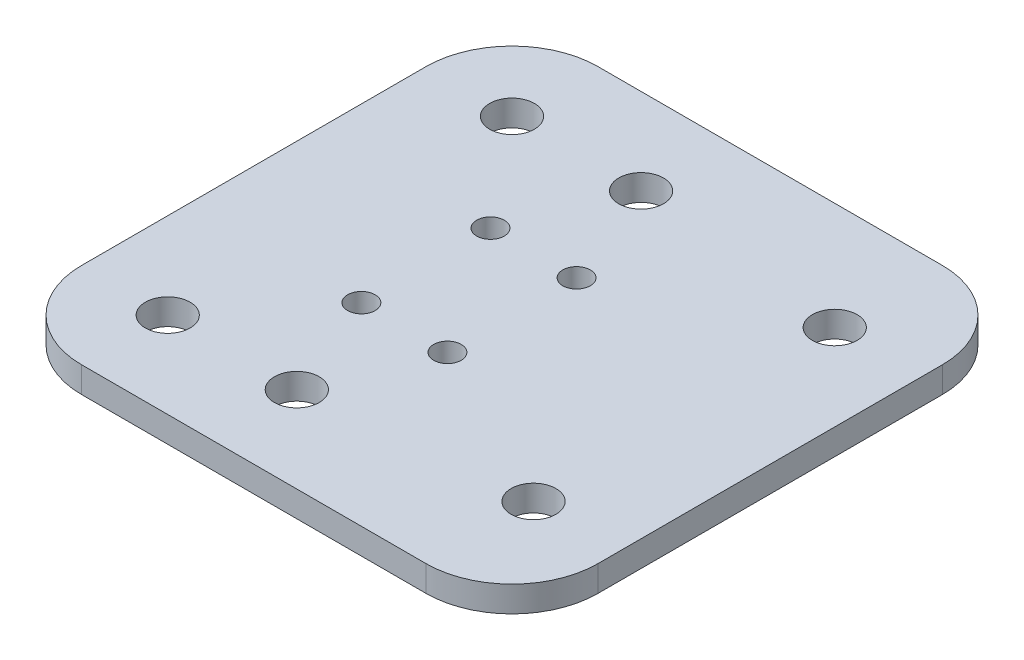
SolidWorks part; units mm, degrees
material "Thornel Mat VMA"
ref_plane "Front" through (0, 0, 0) normal (0, 0, 1) x (1, 0, 0)
ref_plane "Top" through (0, 0, 0) normal (0, 1, 0) x (1, 0, 0)
ref_plane "Right" through (0, 0, 0) normal (1, 0, 0) x (0, 0, -1)
sketch "草图1" plane through (0, 0, 0) normal (0, 1, 0) x (1, 0, 0)
  line L0 (0, -30) -> (0, 30)
  line L1 (0, 30) -> (21.7157, 30)
  line L2 (21.7157, 30) -> (60, 30)
  line L3 (60, 30) -> (60, -30)
  line L4 (0, 0) -> (173.2794, 0) construction
  line L5 (21.7157, -30) -> (60, -30)
  line L6 (0, -30) -> (21.7157, -30)
  point P4 (0, 0)
  point P12 (60, 0)
  dimension "D1" = 60
  dimension "D2" = 30
  dimension "D3" = 60
extrude "凸台-拉伸1" add sketch "草图1" along normal blind 3
sketch "草图2" plane through (0, 3, 0) normal (0, 1, 0) x (1, 0, 0)
  line L0 (20, 7.5) -> (30, 7.5) construction
  line L1 (0, 0) -> (60, 0) construction
  line L2 (60, -30) -> (60, 30) construction
  line L4 (25, 20) -> (25, -20) construction
  line L5 (50, 17.5) -> (50, -17.5) construction
  line L6 (10, 20) -> (10, -20) construction
  line L7 (0, 30) -> (0, -30) construction
  line L8 (60, 30) -> (0, 30) construction
  line L9 (0, -30) -> (60, -30) construction
  line L10 (60, -30) -> (60, 30) construction
  circle A0 centre (20, 7.5) radius 1.6
  circle A1 centre (30, 7.5) radius 1.6
  circle A2 centre (30, -7.5) radius 1.6
  circle A3 centre (20, -7.5) radius 1.6
  circle A4 centre (10, 20) radius 2.6
  circle A5 centre (10, -20) radius 2.6
  circle A8 centre (25, 20) radius 2.6
  circle A9 centre (25, -20) radius 2.6
  circle A10 centre (50, 17.5) radius 2.6
  circle A11 centre (50, -17.5) radius 2.6
  point P31 (25, 0)
  point P33 (50, 0)
  dimension "D1" = 3.2
  dimension "D2" = 3.2
  dimension "D5" = 5.2
  dimension "D6" = 5.2
  dimension "D7" = 10
  dimension "D8" = 10
  dimension "D9" = 10
  dimension "D10" = 10
  dimension "D13" = 5.2
  dimension "D14" = 5.2
  dimension "D15" = 5.2
  dimension "D16" = 5.2
  dimension "D3" = 10
  dimension "D4" = 7.5
  dimension "D11" = 20
  dimension "D12" = 15
  dimension "D17" = 40
  dimension "D18" = 35
extrude "切除-拉伸1" cut sketch "草图2" against normal through all
fillet "圆角1" radius 10 4 edges at (0, 1.5, 30) (0, 1.5, -30) (60, 1.5, 30) (60, 1.5, -30)
